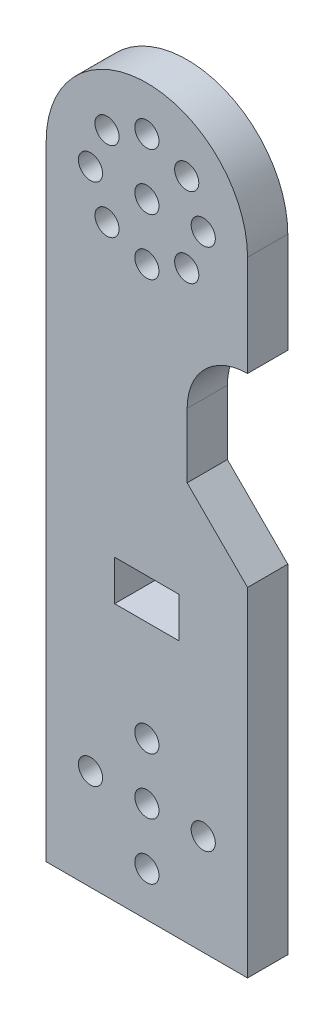
SolidWorks part; units mm, degrees
ref_plane "Front Plane" through (0, 0, 0) normal (0, 0, 1) x (1, 0, 0)
ref_plane "Top Plane" through (0, 0, 0) normal (0, 1, 0) x (1, 0, 0)
ref_plane "Right Plane" through (0, 0, 0) normal (1, 0, 0) x (0, 0, -1)
sketch "Sketch1" plane through (0, 0, 0) normal (0, 0, 1) x (1, 0, 0)
  line L5 (0, 5.5) -> (0, 1.5) construction
  line L6 (-12.5, 0) -> (-12.5, -77.5)
  line L7 (12.5, 0) -> (12.5, -77.5)
  line L12 (0, -77.5) -> (-12.5, -77.5) construction
  line L13 (0, -77.5) -> (12.5, -77.5) construction
  line L15 (-12.5, -77.5) -> (12.5, -77.5)
  circle A1 centre (0, 0) radius 1.5
  circle A8 centre (0, 7) radius 1.5
  circle A15 centre (4.9497, 4.9497) radius 1.5
  circle A16 centre (7, 0) radius 1.5
  circle A17 centre (4.9497, -4.9497) radius 1.5
  circle A18 centre (0, -7) radius 1.5
  circle A19 centre (-4.9497, -4.9497) radius 1.5
  circle A20 centre (-7, 0) radius 1.5
  circle A21 centre (-4.9497, 4.9497) radius 1.5
  arc A22 (12.5, 0) -> (-12.5, 0) centre (0, 0) ccw
  point P8 (0, 12.5)
  point P24 (0, 0)
  dimension "D2" = 3
  dimension "D3" = 3
  dimension "D4" = 4
  dimension "D5" = 8
  dimension "D6" = 90
  dimension "D7" = 25
  dimension "D13" = 12.5
  dimension "D14" = 12.5
extrude "Boss-Extrude1" add sketch "Sketch1" along normal blind 5
sketch "Sketch2" plane through (0, 0, 5) normal (0, 0, 1) x (1, 0, 0)
  line L0 (0, -8.5) -> (0, -77.5) construction
  line L1 (-12.5, -77.5) -> (12.5, -77.5) construction
  line L6 (0, -77.5) -> (0, -43) construction
  line L7 (0, -43) -> (12.5, -43) construction
  line L8 (12.5, 0) -> (12.5, -77.5) construction
  line L10 (-4, -40.5) -> (4, -40.5)
  line L11 (-4, -40.5) -> (-4, -45.5)
  line L12 (-4, -45.5) -> (4, -45.5)
  line L13 (4, -40.5) -> (4, -45.5)
  line L14 (-4, -40.5) -> (4, -45.5) construction
  line L15 (-4, -45.5) -> (4, -40.5) construction
  circle A1 centre (0, -7) radius 1.5 construction
  dimension "D1" = 8
  dimension "D2" = 5
extrude "Cut-Extrude1" cut sketch "Sketch2" against normal blind 10
sketch "Sketch3" plane through (0, 0, 5) normal (0, 0, 1) x (1, 0, 0)
  line L0 (-12.5, -77.5) -> (-12.5, -52.5) construction
  line L4 (-12.5, -52.5) -> (12.5, -52.5)
  line L7 (-12.5, 0) -> (-12.5, -77.5) construction
  line L8 (-12.5, -52.5) -> (-12.5, -65) construction
  line L9 (-12.5, -65) -> (12.5, -65) construction
  line L10 (12.5, 0) -> (12.5, -77.5) construction
  line L11 (-12.5, -52.5) -> (-12.5, -77.5)
  line L12 (-12.5, -77.5) -> (12.5, -77.5)
  line L13 (12.5, -52.5) -> (12.5, -77.5)
  line L14 (-12.5, -52.5) -> (12.5, -77.5) construction
  line L15 (-12.5, -77.5) -> (12.5, -52.5) construction
  line L18 (-10.5, -65) -> (-12.5, -65) construction
  line L20 (10.5, -65) -> (12.5, -65) construction
  circle A0 centre (0, -65) radius 1.5
  circle A1 centre (0, -58) radius 1.5
  circle A2 centre (-7, -65) radius 1.5
  circle A3 centre (7, -65) radius 1.5
  circle A4 centre (0, -72) radius 1.5
  point P2 (0, -65)
  dimension "D2" = 25
  dimension "D5" = 7
  dimension "D4" = 3
  dimension "D7" = 3
  dimension "D1" = 25
  dimension "D3" = 25
  dimension "D6" = 7
extrude "Cut-Extrude2" cut sketch "Sketch3" against normal blind 10
ref_plane "Plane1" through (0, 0, 5) normal (0, 0, 1) x (1, 0, 0)
sketch "Sketch4" plane through (0, 0, 5) normal (0, 0, 1) x (1, 0, 0)
  line L0 (12.5, 0) -> (12.5, -77.5) construction
  line L1 (12.5, -20) -> (5, -20) construction
  line L2 (5, -20) -> (5, -28)
  line L3 (5, -28) -> (12.5, -35.5)
  line L6 (12.5, -27.5) -> (12.5, -35.5)
  circle A0 centre (0, 0) radius 12.5
  arc A1 (12.5, -27.5) -> (5, -20) centre (12.5, -20) ccw
  dimension "D1" = 25
  dimension "D4" = 15
  dimension "D2" = 20
  dimension "D3" = 8
  dimension "D5" = 45
extrude "Cut-Extrude4" cut sketch "Sketch4" against normal blind 10 contours A1 L2 L3 L6
